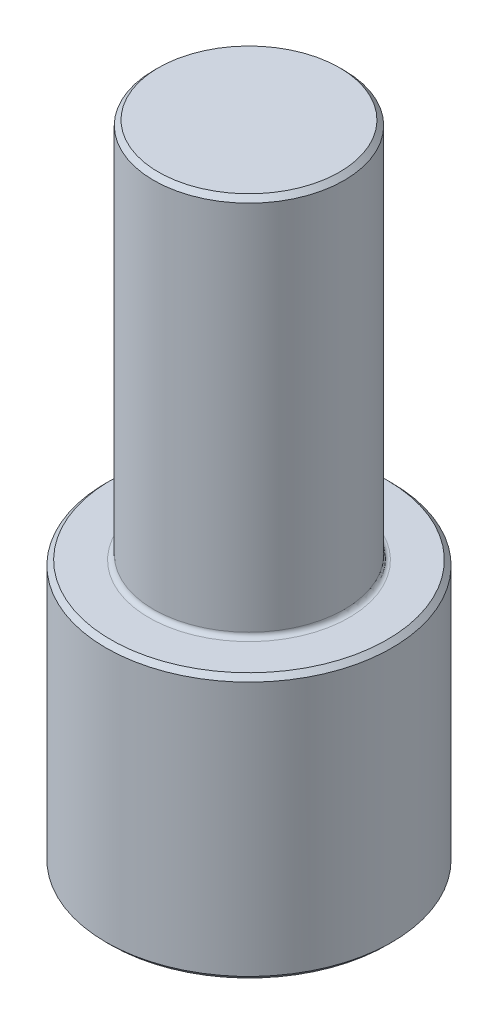
SolidWorks part; units mm, degrees
ref_plane "Front" through (0, 0, 0) normal (0, 0, 1) x (1, 0, 0)
ref_plane "Top" through (0, 0, 0) normal (0, 1, 0) x (1, 0, 0)
ref_plane "Right" through (0, 0, 0) normal (1, 0, 0) x (0, 0, -1)
sketch "Sketch1" plane through (0, 0, 0) normal (0, 0, 1) x (1, 0, 0)
  line L0 (0, 7.4762) -> (0, -8.3651) construction
  line L1 (0, 0) -> (6, 0)
  line L2 (6, 0) -> (6, 11.1)
  line L3 (6, 11.1) -> (4, 11.1)
  line L4 (4, 11.1) -> (4, 27.1)
  line L5 (4, 27.1) -> (0, 27.1)
  line L6 (0, 27.1) -> (0, 0)
  line L7 (117.174, 11.1) -> (6.584, 11.1) construction
  dimension "D1" = 0
  dimension "D2" = 16
  dimension "D3" = 4
  dimension "D4" = 2
revolve "Revolve1" add sketch "Sketch1" angle 360 about L0
hole_wizard "M4 Tapped Hole1" positions "Sketch2" profile "Sketch4" tap size "M4" standard "ISO"
sketch "Sketch2" plane through (0, 0, 0) normal (0, -1, 0) x (-1, 0, 0)
  point P0 (0, 0)
sketch "Sketch4" plane through (0, 0, 0) normal (1, 0, 0) x (0, 0, -1)
  line L0 (0, 0) -> (0, 12.9914)
  line L1 (0, 12.9914) -> (1.65, 12)
  line L2 (1.65, 12) -> (1.65, 0)
  line L5 (1.65, 0) -> (0, 0)
  line L10 (0, 12.9914) -> (-1.65, 12) construction
  line L11 (0, -6.35) -> (0, 107.95) construction
  dimension "Tap Drill Dia." = 3.3
  dimension "Tap Drill Depth" = 12
  dimension "Drill Angle" = 118
cosmetic thread "Hole Thread1" parameters "D1"=8, "D2"=4
ref_plane "Plane1" through (0, 13.55, 0) normal (0, -1, 0) x (-1, 0, 0)
fillet "Fillet1" radius 0.2 1 edges at (0, 11.1, 4)
chamfer "Chamfer1" distance 0.2 angle 45 3 edges at (0, 0, 6) (0, 11.1, 6) (0, 27.1, 4)
